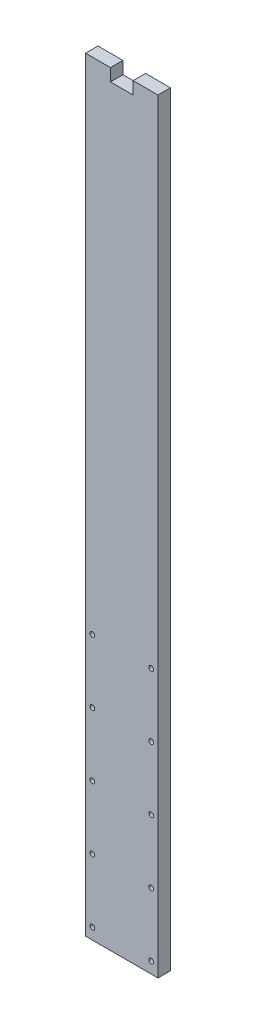
SolidWorks part; units mm, degrees
material "ﾁｰｸ材"
ref_plane "正面" through (0, 0, 0) normal (0, 0, 1) x (1, 0, 0)
ref_plane "平面" through (0, 0, 0) normal (0, 1, 0) x (1, 0, 0)
ref_plane "右側面" through (0, 0, 0) normal (1, 0, 0) x (0, 0, -1)
sketch "ｽｹｯﾁ1" plane through (0, 0, 0) normal (0, 0, 1) x (1, 0, 0)
  line L1 (0, 0) -> (32, 0)
  line L2 (0, 0) -> (0, 338)
  line L3 (0, 338) -> (32, 338)
  line L4 (32, 0) -> (32, 338)
  dimension "D1" = 32
  dimension "D2" = 338
extrude "ﾎﾞｽ - 押し出し1" add sketch "ｽｹｯﾁ1" along normal blind 5.5
sketch "ｽｹｯﾁ2" plane through (0, 0, 5.5) normal (0, 0, 1) x (1, 0, 0)
  line L0 (32, 338) -> (0, 338) construction
  line L1 (11, 332.5) -> (21, 332.5)
  line L2 (11, 332.5) -> (11, 338)
  line L3 (11, 338) -> (21, 338)
  line L4 (21, 332.5) -> (21, 338)
  line L5 (11, 332.5) -> (21, 338) construction
  line L6 (11, 338) -> (21, 332.5) construction
  line L7 (0, 338) -> (0, 0) construction
  point P0 (16, 335.25)
  point P7 (16, 338)
  dimension "D1" = 10
  dimension "D2" = 5.5
  dimension "D3" = 16
extrude "ｶｯﾄ - 押し出し1" cut sketch "ｽｹｯﾁ2" against normal blind 5.5
sketch "ｽｹｯﾁ3" plane through (0, 0, 5.5) normal (0, 0, 1) x (1, 0, 0)
  line L0 (0, 0) -> (32, 0) construction
  line L1 (3, 5) -> (3, 33) construction
  circle A0 centre (3, 5) radius 1.05
  circle A1 centre (29, 5) radius 1.05
  circle A2 centre (3, 33) radius 1.05
  circle A3 centre (29, 33) radius 1.05
  circle A4 centre (3, 61) radius 1.05
  circle A5 centre (29, 61) radius 1.05
  circle A6 centre (3, 89) radius 1.05
  circle A7 centre (29, 89) radius 1.05
  circle A8 centre (3, 117) radius 1.05
  circle A9 centre (29, 117) radius 1.05
  point P6 (16, 0)
  dimension "D1" = 2.1
  dimension "D2" = 13
  dimension "D3" = 13
  dimension "D4" = 5
  dimension "D6" = 28
  dimension "D5" = 5
extrude "ｶｯﾄ - 押し出し2" cut sketch "ｽｹｯﾁ3" against normal blind 10
